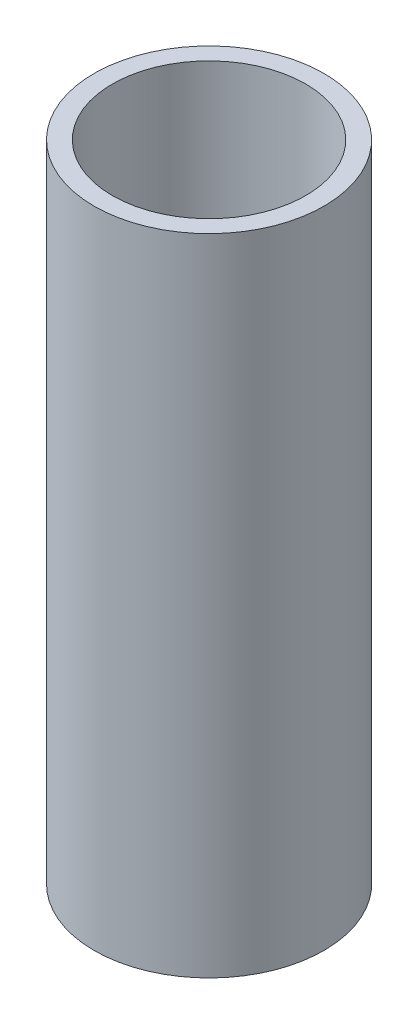
SolidWorks part; units mm, degrees
ref_plane "Front Plane" through (0, 0, 0) normal (0, 0, 1) x (1, 0, 0)
ref_plane "Top Plane" through (0, 0, 0) normal (0, 1, 0) x (1, 0, 0)
ref_plane "Right Plane" through (0, 0, 0) normal (1, 0, 0) x (0, 0, -1)
sketch "Sketch1" plane through (0, 0, 0) normal (0, 1, 0) x (1, 0, 0)
  circle A0 centre (0, 0) radius 0.535
  circle A1 centre (0, 0) radius 0.45
  dimension "D1" = 1.07
  dimension "D2" = 0.9
extrude "Boss-Extrude1" add sketch "Sketch1" along normal blind 3
